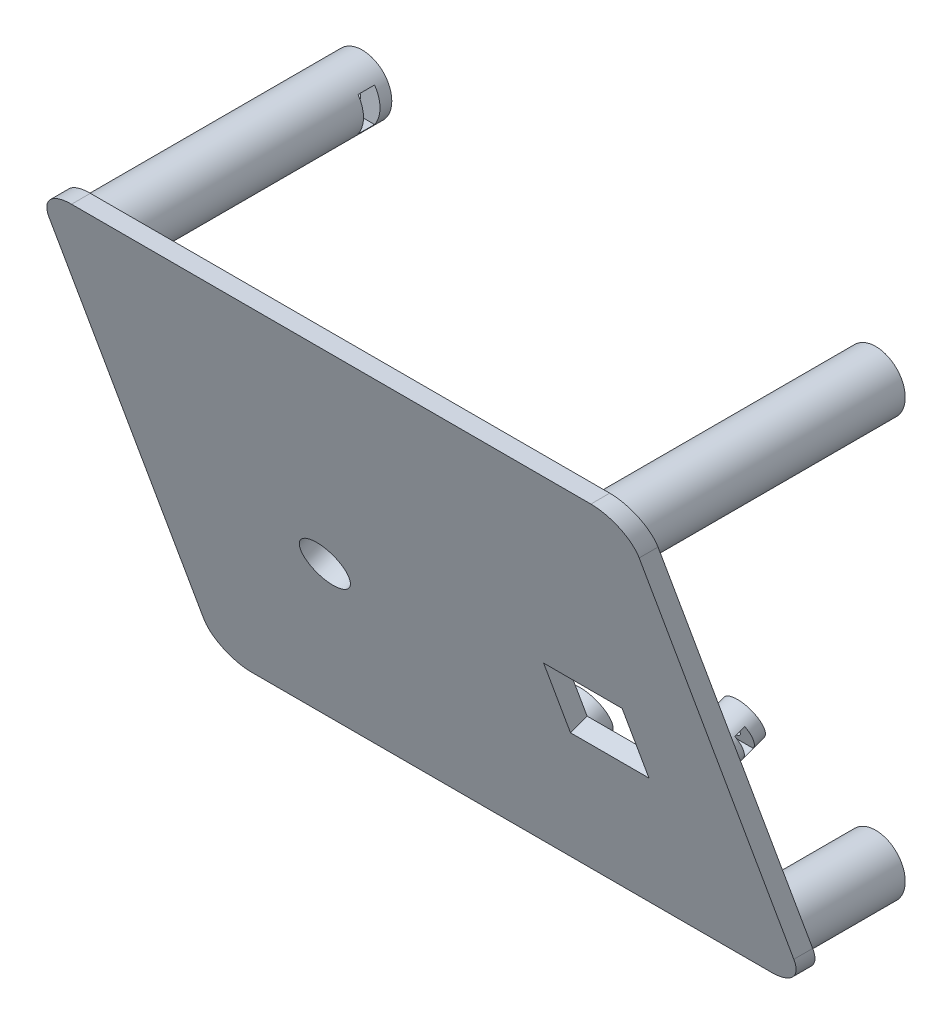
SolidWorks part; units mm, degrees
ref_plane "前视基准面" through (0, 0, 0) normal (0, 0, 1) x (1, 0, 0)
ref_plane "上视基准面" through (0, 0, 0) normal (0, 1, 0) x (1, 0, 0)
ref_plane "右视基准面" through (0, 0, 0) normal (1, 0, 0) x (0, 0, -1)
other "Configuration Table"
sketch "草图1" plane through (0, 0, 0) normal (0, 0, 1) x (1, 0, 0)
  line L0 (6, 0) -> (94, 0)
  line L1 (100, 6) -> (100, 78)
  line L2 (94, 84) -> (6, 84)
  line L3 (0, 78) -> (0, 6)
  arc A0 (94, 0) -> (100, 6) centre (94, 6) ccw
  arc A1 (100, 78) -> (94, 84) centre (94, 78) ccw
  arc A2 (6, 84) -> (0, 78) centre (6, 78) ccw
  arc A3 (0, 6) -> (6, 0) centre (6, 6) ccw
extrude "Lid_blank" add sketch "草图1" along normal blind 56
sketch "草图2" plane through (0, 0, 0) normal (1, 0, 0) x (0, 0, -1)
  line L0 (-13.9131, -20) -> (-61.2293, 110)
  line L1 (-61.2293, 110) -> (-120, 110)
  line L2 (-120, 110) -> (-120, -20)
  line L3 (-120, -20) -> (-13.9131, -20)
extrude "Outer_panel_20deg" cut sketch "草图2" against normal through all and the other way through all
sketch "草图3" plane through (0, 0, 0) normal (1, 0, 0) x (0, 0, -1)
  line L0 (-10.7206, -20) -> (-58.0367, 110)
  line L1 (-58.0367, 110) -> (30, 110)
  line L2 (30, 110) -> (30, -20)
  line L3 (30, -20) -> (-10.7206, -20)
extrude "Panel_3mm" cut sketch "草图3" against normal through all and the other way through all
sketch "草图4" plane through (0, 0, 0) normal (0, 0, 1) x (1, 0, 0)
  circle A0 centre (6.5, 6.5) radius 5
extrude "Hidden_case_post_0" add sketch "草图4" along normal blind 22.8782 from offset 3
sketch "草图5" plane through (0, 0, 0) normal (0, 0, 1) x (1, 0, 0)
  circle A0 centre (93.5, 6.5) radius 5
extrude "Hidden_case_post_1" add sketch "草图5" along normal blind 22.8782 from offset 3
sketch "草图6" plane through (0, 0, 0) normal (0, 0, 1) x (1, 0, 0)
  circle A0 centre (6.5, 77.5) radius 5
extrude "Hidden_case_post_2" add sketch "草图6" along normal blind 48.7201 from offset 3
sketch "草图7" plane through (0, 0, 0) normal (0, 0, 1) x (1, 0, 0)
  circle A0 centre (93.5, 77.5) radius 5
extrude "Hidden_case_post_3" add sketch "草图7" along normal blind 48.7201 from offset 3
sketch "草图8" plane through (0, 0, 0) normal (1, 0, 0) x (0, 0, -1)
  line L0 (-13.9131, -20) -> (-61.2293, 110)
  line L1 (-61.2293, 110) -> (-120, 110)
  line L2 (-120, 110) -> (-120, -20)
  line L3 (-120, -20) -> (-13.9131, -20)
extrude "Flush_outer_surface" cut sketch "草图8" against normal through all and the other way through all
sketch "草图9" plane through (0, 0, 0) normal (0, 0, 1) x (1, 0, 0)
  circle A0 centre (6.5, 6.5) radius 1.7
extrude "Blind_M3_0" cut sketch "草图9" along normal blind 9.5 from offset 3
sketch "草图10" plane through (0, 0, 0) normal (1, 0, 0) x (0, 0, -1)
  line L0 (-5, 3.6) -> (-5, 9.4)
  line L1 (-5, 9.4) -> (-7.8, 9.4)
  line L2 (-7.8, 9.4) -> (-7.8, 3.6)
  line L3 (-7.8, 3.6) -> (-5, 3.6)
extrude "M3_side_load_nut_0" cut sketch "草图10" along normal blind 9.4 from offset 3.1
sketch "草图11" plane through (0, 0, 0) normal (0, 0, 1) x (1, 0, 0)
  circle A0 centre (93.5, 6.5) radius 1.7
extrude "Blind_M3_1" cut sketch "草图11" along normal blind 9.5 from offset 3
sketch "草图12" plane through (0, 0, 0) normal (1, 0, 0) x (0, 0, -1)
  line L0 (-5, 3.6) -> (-5, 9.4)
  line L1 (-5, 9.4) -> (-7.8, 9.4)
  line L2 (-7.8, 9.4) -> (-7.8, 3.6)
  line L3 (-7.8, 3.6) -> (-5, 3.6)
extrude "M3_side_load_nut_1" cut sketch "草图12" along normal blind 9.4 from offset 87.5
sketch "草图13" plane through (0, 0, 0) normal (0, 0, 1) x (1, 0, 0)
  circle A0 centre (6.5, 77.5) radius 1.7
extrude "Blind_M3_2" cut sketch "草图13" along normal blind 9.5 from offset 3
sketch "草图14" plane through (0, 0, 0) normal (1, 0, 0) x (0, 0, -1)
  line L0 (-5, 74.6) -> (-5, 80.4)
  line L1 (-5, 80.4) -> (-7.8, 80.4)
  line L2 (-7.8, 80.4) -> (-7.8, 74.6)
  line L3 (-7.8, 74.6) -> (-5, 74.6)
extrude "M3_side_load_nut_2" cut sketch "草图14" along normal blind 9.4 from offset 3.1
sketch "草图15" plane through (0, 0, 0) normal (0, 0, 1) x (1, 0, 0)
  circle A0 centre (93.5, 77.5) radius 1.7
extrude "Blind_M3_3" cut sketch "草图15" along normal blind 9.5 from offset 3
sketch "草图16" plane through (0, 0, 0) normal (1, 0, 0) x (0, 0, -1)
  line L0 (-5, 74.6) -> (-5, 80.4)
  line L1 (-5, 80.4) -> (-7.8, 80.4)
  line L2 (-7.8, 80.4) -> (-7.8, 74.6)
  line L3 (-7.8, 74.6) -> (-5, 74.6)
extrude "M3_side_load_nut_3" cut sketch "草图16" along normal blind 9.4 from offset 87.5
sketch "草图17" plane through (0, -6.8111, 18.7135) normal (0, -0.342, 0.9397) x (1, 0, 0)
  circle A0 centre (31, 44.2483) radius 4.1
extrude "Shaft_D8p2" cut sketch "草图17" against normal blind 5
sketch "草图18" plane through (0, -6.8111, 18.7135) normal (0, -0.342, 0.9397) x (1, 0, 0)
  line L0 (70.35, 37.5983) -> (83.65, 37.5983)
  line L1 (83.65, 37.5983) -> (83.65, 50.8983)
  line L2 (83.65, 50.8983) -> (70.35, 50.8983)
  line L3 (70.35, 50.8983) -> (70.35, 37.5983)
extrude "Button_13p3_clearance" cut sketch "草图18" against normal blind 5
sketch "草图19" plane through (0, -5.7851, 15.8944) normal (0, 0.342, -0.9397) x (-1, 0, 0)
  circle A0 centre (-23, 30.7483) radius 4
extrude "Encoder_front_blind_post" add sketch "草图19" along normal blind 11.07
sketch "草图20" plane through (0, -6.8111, 18.7135) normal (0, -0.342, 0.9397) x (1, 0, 0)
  circle A0 centre (23, 30.7483) radius 1.15
extrude "Encoder_front_blind_screw" cut sketch "草图20" along normal blind 5 from offset 14.07
sketch "草图21" plane through (0, 0, 0) normal (1, 0, 0) x (0, 0, -1)
  line L0 (-17.1697, 24.2376) -> (-18.6062, 28.1843)
  line L1 (-18.6062, 28.1843) -> (-20.2976, 27.5687)
  line L2 (-20.2976, 27.5687) -> (-18.8611, 23.622)
  line L3 (-18.8611, 23.622) -> (-17.1697, 24.2376)
extrude "Encoder_front_M2_side_nut" cut sketch "草图21" along normal blind 7.5 from offset 20.5
sketch "草图22" plane through (0, -5.7851, 15.8944) normal (0, 0.342, -0.9397) x (-1, 0, 0)
  circle A0 centre (-47, 57.7483) radius 4
extrude "Encoder_rear_blind_post" add sketch "草图22" along normal blind 11.07
sketch "草图23" plane through (0, -6.8111, 18.7135) normal (0, -0.342, 0.9397) x (1, 0, 0)
  circle A0 centre (47, 57.7483) radius 1.15
extrude "Encoder_rear_blind_screw" cut sketch "草图23" along normal blind 5 from offset 14.07
sketch "草图24" plane through (0, 0, 0) normal (1, 0, 0) x (0, 0, -1)
  line L0 (-26.4042, 49.6093) -> (-27.8407, 53.556)
  line L1 (-27.8407, 53.556) -> (-29.5321, 52.9404)
  line L2 (-29.5321, 52.9404) -> (-28.0957, 48.9937)
  line L3 (-28.0957, 48.9937) -> (-26.4042, 49.6093)
extrude "Encoder_rear_M2_side_nut" cut sketch "草图24" along normal blind 7.5 from offset 44.5
sketch "草图25" plane through (0, -5.7851, 15.8944) normal (0, 0.342, -0.9397) x (-1, 0, 0)
  circle A0 centre (-60, 25.2483) radius 4
extrude "Button_left_blind_post" add sketch "草图25" along normal blind 6.7
sketch "草图26" plane through (0, -6.8111, 18.7135) normal (0, -0.342, 0.9397) x (1, 0, 0)
  circle A0 centre (60, 25.2483) radius 1.15
extrude "Button_left_blind_screw" cut sketch "草图26" along normal blind 5 from offset 9.7
sketch "草图27" plane through (0, 0, 0) normal (1, 0, 0) x (0, 0, -1)
  line L0 (-19.395, 17.5747) -> (-20.8315, 21.5214)
  line L1 (-20.8315, 21.5214) -> (-22.523, 20.9057)
  line L2 (-22.523, 20.9057) -> (-21.0865, 16.959)
  line L3 (-21.0865, 16.959) -> (-19.395, 17.5747)
extrude "Button_left_M2_side_nut" cut sketch "草图27" along normal blind 7.5 from offset 57.5
sketch "草图28" plane through (0, -5.7851, 15.8944) normal (0, 0.342, -0.9397) x (-1, 0, 0)
  circle A0 centre (-93.3, 45.2483) radius 3.4
extrude "Button_right_blind_post" add sketch "草图28" along normal blind 6.7
sketch "草图29" plane through (0, -6.8111, 18.7135) normal (0, -0.342, 0.9397) x (1, 0, 0)
  circle A0 centre (93.3, 45.2483) radius 1.15
extrude "Button_right_blind_screw" cut sketch "草图29" along normal blind 5 from offset 9.7
sketch "草图30" plane through (0, 0, 0) normal (1, 0, 0) x (0, 0, -1)
  line L0 (-26.2354, 36.3685) -> (-27.6719, 40.3152)
  line L1 (-27.6719, 40.3152) -> (-29.3634, 39.6996)
  line L2 (-29.3634, 39.6996) -> (-27.9269, 35.7529)
  line L3 (-27.9269, 35.7529) -> (-26.2354, 36.3685)
extrude "Button_right_M2_side_nut" cut sketch "草图30" along normal blind 7.5 from offset 90.8
